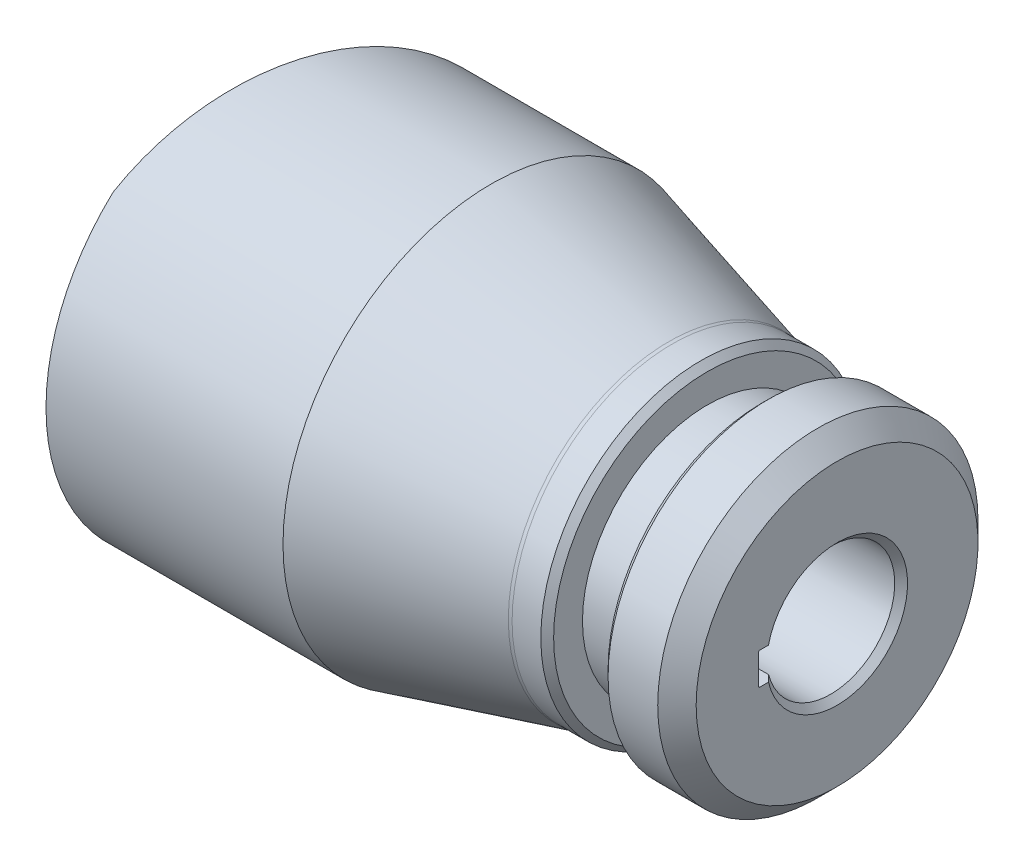
SolidWorks part; units mm, degrees
ref_plane "Спереди" through (0, 0, 0) normal (0, 0, 1) x (1, 0, 0)
ref_plane "Сверху" through (0, 0, 0) normal (0, 1, 0) x (1, 0, 0)
ref_plane "Справа" through (0, 0, 0) normal (1, 0, 0) x (0, 0, -1)
other "Configuration Table"
sketch "Эскиз1" plane through (0, 0, 0) normal (0, 0, 1) x (1, 0, 0)
  line L0 (0, 32.5) -> (37, 32.5)
  line L1 (37, 32.5) -> (64.7457, 25.0681)
  line L2 (65.2632, 25) -> (69.75, 25)
  line L3 (69.75, 25) -> (70.75, 24)
  line L4 (70.75, 24) -> (70.75, 19.5)
  line L5 (70.75, 19.5) -> (79.25, 19.5)
  line L6 (79.25, 19.5) -> (79.25, 24)
  line L7 (79.25, 24) -> (80.25, 25)
  line L8 (80.25, 25) -> (88, 25)
  line L9 (88, 25) -> (91, 22)
  line L10 (91, 22) -> (91, 11)
  line L11 (91, 11) -> (90, 10)
  line L12 (90, 10) -> (61, 10)
  line L13 (61, 10) -> (61, 19)
  line L14 (60, 20) -> (25, 20)
  line L15 (25, 20) -> (25, 27.1)
  line L16 (24.6, 27.5) -> (0, 27.5)
  line L17 (0, 27.5) -> (0, 32.5)
  line L18 (0, 0) -> (100, 0) construction
  arc A0 (64.7457, 25.0681) -> (65.2632, 25) centre (65.2632, 27) ccw
  arc A1 (61, 19) -> (60, 20) centre (60, 19) ccw
  arc A2 (25, 27.1) -> (24.6, 27.5) centre (24.6, 27.1) ccw
revolve "Точеный профиль" add sketch "Эскиз1" angle 360 about L18
sketch "Эскиз2" plane through (0, 0, 0) normal (0, 1, 0) x (1, 0, 0)
  line L0 (-25, 50) -> (15.3041, 50)
  line L1 (15.3041, 50) -> (-5.9516, -50)
  line L2 (-5.9516, -50) -> (-25, -50)
  line L3 (-25, -50) -> (-25, 50)
extrude "Наклон торца 12 градусов" cut sketch "Эскиз2" against normal through all and the other way through all
sketch "Эскиз3" plane through (0, 0, 0) normal (1, 0, 0) x (0, 0, -1)
  line L0 (0, -2.5) -> (0, 2.5)
  line L1 (0, 2.5) -> (-12.05, 2.5)
  line L2 (-12.3, 2.25) -> (-12.3, -2.25)
  line L3 (-12.05, -2.5) -> (0, -2.5)
  arc A0 (-12.05, 2.5) -> (-12.3, 2.25) centre (-12.05, 2.25) ccw
  arc A1 (-12.3, -2.25) -> (-12.05, -2.5) centre (-12.05, -2.25) ccw
extrude "Паз 5 R0.25" cut sketch "Эскиз3" along normal blind 31 from offset 61
ref_plane "Плоскость отверстий 30" through (0, 0, 0) normal (0, -0.5, 0.866) x (1, 0, 0)
sketch "Эскиз4" plane through (0, 0, 0) normal (0, -0.5, 0.866) x (1, 0, 0)
  line L0 (17, -26) -> (18.7, -26)
  line L1 (18.7, -26) -> (18.7, -29.5)
  line L2 (18.7, -29.5) -> (20.5, -29.5)
  line L3 (20.5, -29.5) -> (20.5, -40)
  line L4 (20.5, -40) -> (17, -40)
  line L5 (17, -40) -> (17, -26)
  line L6 (17, -20) -> (17, -45) construction
